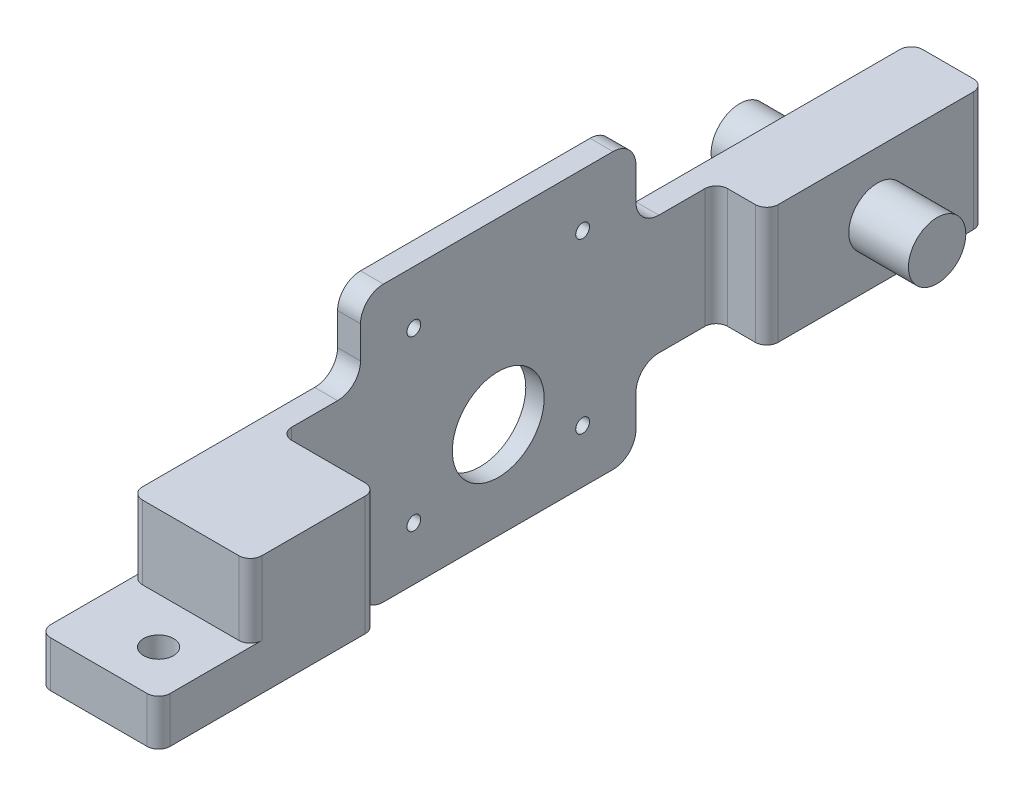
SolidWorks part; units mm, degrees
ref_plane "前视基准面" through (0, 0, 0) normal (0, 0, 1) x (1, 0, 0)
ref_plane "上视基准面" through (0, 0, 0) normal (0, 1, 0) x (1, 0, 0)
ref_plane "右视基准面" through (0, 0, 0) normal (1, 0, 0) x (0, 0, -1)
other "Configuration Table"
ref_plane "基准面1" through (0, 26, 0) normal (0, 1, 0) x (1, 0, 0)
sketch "草图1" plane through (0, 26, 0) normal (0, 1, 0) x (1, 0, 0)
  line L0 (52, -190) -> (52, 190)
  line L1 (52, 190) -> (0, 190)
  line L2 (0, 190) -> (0, -190)
  line L3 (0, -190) -> (52, -190)
extrude "凸台-拉伸1" add sketch "草图1" against normal blind 52
sketch "草图2" plane through (0, 26, 0) normal (0, 1, 0) x (-1, 0, 0)
  line L0 (-10, -190) -> (-10, 95)
  line L1 (-10, 95) -> (-52, 95)
  line L2 (-52, 95) -> (-52, -190)
  line L3 (-52, -190) -> (-10, -190)
extrude "切除-拉伸1" cut sketch "草图2" against normal through all
sketch "草图3" plane through (10, 0, 0) normal (1, 0, 0) x (0, 0, -1)
  line L0 (190, -26) -> (95, -26)
  line L1 (95, -26) -> (95, 26)
  line L2 (95, 26) -> (190, 26)
  line L3 (190, 26) -> (190, -26)
extrude "凸台-拉伸2" add sketch "草图3" along normal blind 22
sketch "草图4" plane through (0, 26, 0) normal (0, 1, 0) x (-1, 0, 0)
  line L0 (0, 60) -> (0, -60)
  line L1 (0, -60) -> (-10, -60)
  line L2 (-10, -60) -> (-10, 60)
  line L3 (-10, 60) -> (0, 60)
extrude "凸台-拉伸3" add sketch "草图4" along normal blind 34
sketch "草图5" plane through (0, -26, 0) normal (0, -1, 0) x (1, 0, 0)
  line L0 (0, -60) -> (0, 60)
  line L1 (0, 60) -> (10, 60)
  line L2 (10, 60) -> (10, -60)
  line L3 (10, -60) -> (0, -60)
extrude "凸台-拉伸4" add sketch "草图5" along normal blind 34
sketch "草图6" plane through (0, 0, 0) normal (-1, 0, 0) x (0, 0, 1)
  line L0 (190, 26) -> (150, 26)
  line L1 (150, 26) -> (150, -6)
  line L2 (150, -6) -> (190, -6)
  line L3 (190, -6) -> (190, 26)
extrude "切除-拉伸2" cut sketch "草图6" against normal through all
sketch "草图7" plane through (0, 0, 0) normal (-1, 0, 0) x (0, 0, 1)
  line L0 (-45.5, 45.5) -> (-45.5, -45.5)
  line L1 (-45.5, -45.5) -> (45.5, -45.5)
  line L2 (45.5, -45.5) -> (45.5, 45.5)
  line L3 (45.5, 45.5) -> (-45.5, 45.5)
extrude "切除-拉伸3" cut sketch "草图7" against normal blind 2
ref_plane "基准面2" through (0, 0, -143.248) normal (0, 0, 1) x (1, 0, 0)
sketch "草图8" plane through (0, 0, -143.248) normal (0, 0, 1) x (1, 0, 0)
  line L0 (-28, 12.5) -> (-28, 0)
  line L1 (-28, 0) -> (0, 0)
  line L2 (0, 0) -> (0, 12.5)
  line L3 (0, 12.5) -> (-28, 12.5)
  line L4 (-28, 0) -> (0, 0) construction
revolve "旋转1" add sketch "草图8" angle 360 about L4
sketch "草图9" plane through (0, 0, -143.248) normal (0, 0, 1) x (1, 0, 0)
  line L0 (32, 12.5) -> (32, 0)
  line L1 (32, 0) -> (58, 0)
  line L2 (58, 0) -> (58, 12.5)
  line L3 (58, 12.5) -> (32, 12.5)
  line L4 (32, 0) -> (58, 0) construction
revolve "旋转2" add sketch "草图9" angle 360 about L4
hole_wizard "Ø13.0 (13) 直径孔1" positions "草图11" profile "草图10" hole size "Ø13.0" standard "ANSI Metric"
sketch "草图11" plane through (0, -26, 0) normal (0, -1, 0) x (-1, 0, 0)
  point P0 (-32, -170)
sketch "草图10" plane through (32, -26, 170) normal (1, 0, 0) x (0, 0, -1)
  line L0 (0, 0) -> (0, 86)
  line L1 (0, 86) -> (6.5, 86)
  line L2 (6.5, 86) -> (6.5, 0)
  line L5 (6.5, 0) -> (0, 0)
  line L11 (0, -6.35) -> (0, 107.95) construction
  dimension "通孔孔直径" = 13
  dimension "通孔孔深度" = 86
hole_wizard "M39 螺旋的螺纹孔钻头1" positions "草图13" profile "草图12" hole size "M39x3.0" standard "ANSI Metric"
sketch "草图13" plane through (10, 0, 0) normal (1, 0, 0) x (0, 0, -1)
  point P0 (0, -18)
sketch "草图12" plane through (10, -18, 0) normal (0, 1, 0) x (0, 0, -1)
  line L0 (0, 0) -> (0, 38)
  line L1 (0, 38) -> (20, 38)
  line L2 (20, 38) -> (20, 0)
  line L5 (20, 0) -> (0, 0)
  line L11 (0, -6.35) -> (0, 107.95) construction
  dimension "通孔孔直径" = 40
  dimension "通孔孔深度" = 38
hole_wizard "Ø6.0 (6) 直径孔1" positions "草图15" profile "草图14" hole size "Ø6.0" standard "ANSI Metric"
sketch "草图15" plane through (10, 0, 0) normal (1, 0, 0) x (0, 0, -1)
  point P0 (36.77, 36.77)
  point P1 (36.77, -36.77)
  point P2 (-36.77, -36.77)
  point P3 (-36.77, 36.77)
sketch "草图14" plane through (10, 36.77, -36.77) normal (0, 1, 0) x (0, 0, -1)
  line L0 (0, 0) -> (0, 38)
  line L1 (0, 38) -> (3, 38)
  line L2 (3, 38) -> (3, 0)
  line L5 (3, 0) -> (0, 0)
  line L11 (0, -6.35) -> (0, 107.95) construction
  dimension "通孔孔直径" = 6
  dimension "通孔孔深度" = 38
fillet "圆角1" radius 5 14 edges at (32, 0, -190) (1, 45.5, 45.5) (52, 0, 95) (0, 10, 150) (1, -45.5, -45.5) (52, -16, 190) (10, 0, -95) (10, 0, 95) (1, 45.5, -45.5) (52, 10, 150) (1, -45.5, 45.5) (32, 0, -95) (0, -16, 190) (0, 0, -190)
fillet "圆角2" radius 10 8 edges at (5, 26, 60) (5, 26, -60) (5, 60, 60) (5, 60, -60) (5, -26, -60) (5, -26, 60) (5, -60, -60) (5, -60, 60)
